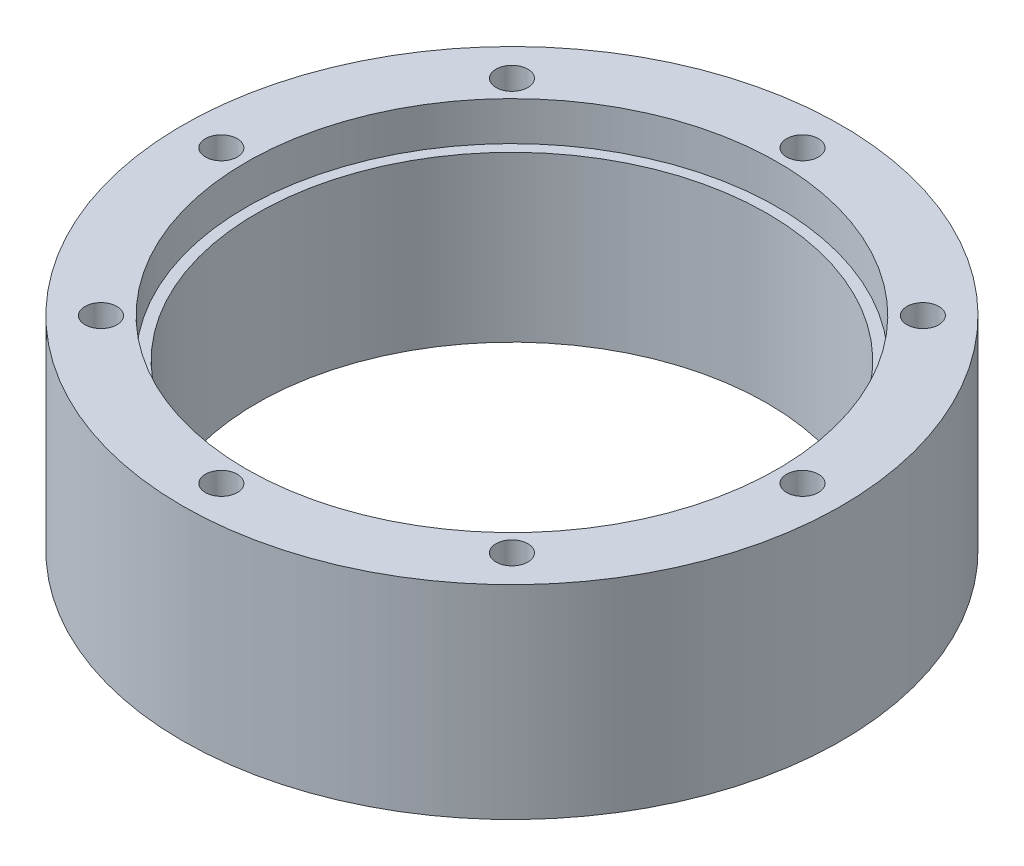
SolidWorks part; units mm, degrees
ref_plane "Front Plane" through (0, 0, 0) normal (0, 0, 1) x (1, 0, 0)
ref_plane "Top Plane" through (0, 0, 0) normal (0, 1, 0) x (1, 0, 0)
ref_plane "Right Plane" through (0, 0, 0) normal (1, 0, 0) x (0, 0, -1)
sketch "Sketch1" plane through (0, 0, 0) normal (0, 1, 0) x (1, 0, 0)
  circle A0 centre (0, 0) radius 46.5
  circle A1 centre (0, 0) radius 36
  dimension "D1" = 93
  dimension "D2" = 72
extrude "Boss-Extrude1" add sketch "Sketch1" along normal blind 28.7
sketch "Sketch2" plane through (0, 28.7, 0) normal (0, 1, 0) x (1, 0, 0)
  circle A0 centre (0, 0) radius 41 construction
  circle A1 centre (0, 41) radius 2.25
  circle A2 centre (28.9914, 28.9914) radius 2.25
  circle A3 centre (41, 0) radius 2.25
  circle A4 centre (28.9914, -28.9914) radius 2.25
  circle A5 centre (0, -41) radius 2.25
  circle A6 centre (-28.9914, -28.9914) radius 2.25
  circle A7 centre (-41, 0) radius 2.25
  circle A8 centre (-28.9914, 28.9914) radius 2.25
  point P22 (0, 0)
  dimension "D1" = 82
  dimension "D2" = 4.5
  dimension "D3" = 8
extrude "Cut-Extrude1" cut sketch "Sketch2" against normal through all
sketch "Sketch3" plane through (0, 28.7, 0) normal (0, 1, 0) x (1, 0, 0)
  circle A0 centre (0, 0) radius 36 construction
  circle A1 centre (0, 0) radius 36
  circle A2 centre (0, 0) radius 37.5
  dimension "D1" = 75
extrude "Cut-Extrude2" cut sketch "Sketch3" against normal blind 5.5
